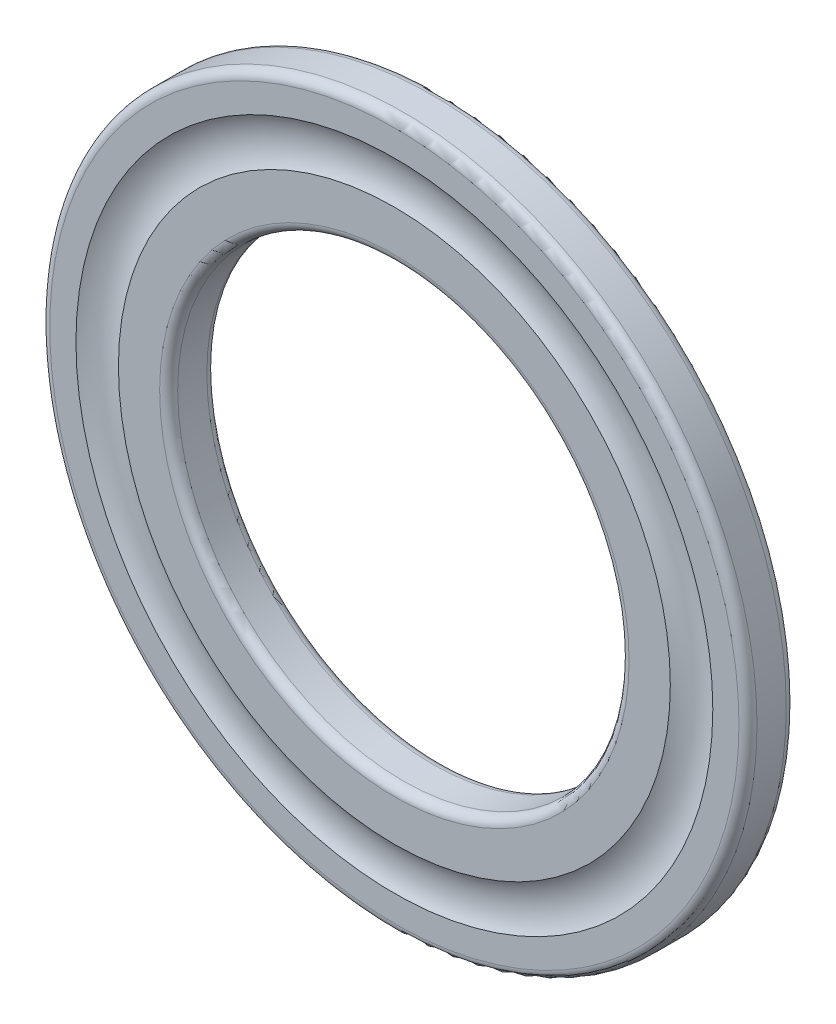
SolidWorks part; units mm, degrees
ref_plane "Plan de face" through (0, 0, 0) normal (0, 0, 1) x (1, 0, 0)
ref_plane "Plan de dessus" through (0, 0, 0) normal (0, 1, 0) x (1, 0, 0)
ref_plane "Plan de droite" through (0, 0, 0) normal (1, 0, 0) x (0, 0, -1)
sketch "Esquisse1" plane through (0, 0, 0) normal (0, 0, 1) x (1, 0, 0)
  circle A0 centre (0, 0) radius 23.5
  circle A1 centre (0, 0) radius 15
  dimension "D1" = 47
  dimension "D2" = 30
extrude "Boss.-Extru.1" add sketch "Esquisse1" along normal blind 3.14
sketch "Esquisse2" plane through (0, 0, 0) normal (0, 1, 0) x (1, 0, 0)
  line L0 (0, 0) -> (0, -11) construction
  line L1 (23.5, 0) -> (-23.5, 0) construction
  line L2 (16, -1.57) -> (23.5, -1.57) construction
  line L4 (23.5, -3.14) -> (23.5, 0) construction
  line L5 (0, -5.5) -> (19.75, -5.5) construction
  circle A0 centre (19.75, -5.5) radius 2.75
  point P13 (19.75, -1.57)
  dimension "D2" = 5.5
  dimension "D1" = 11
  dimension "D3" = 19.75
revolve "Enlèvement de matière-Révolution1" cut sketch "Esquisse2" angle 360 about L0
fillet "Congé1" radius 0.6 4 edges at (15, 0, 0) (15, 0, 3.14) (23.5, 0, 0) (23.5, 0, 3.14)
